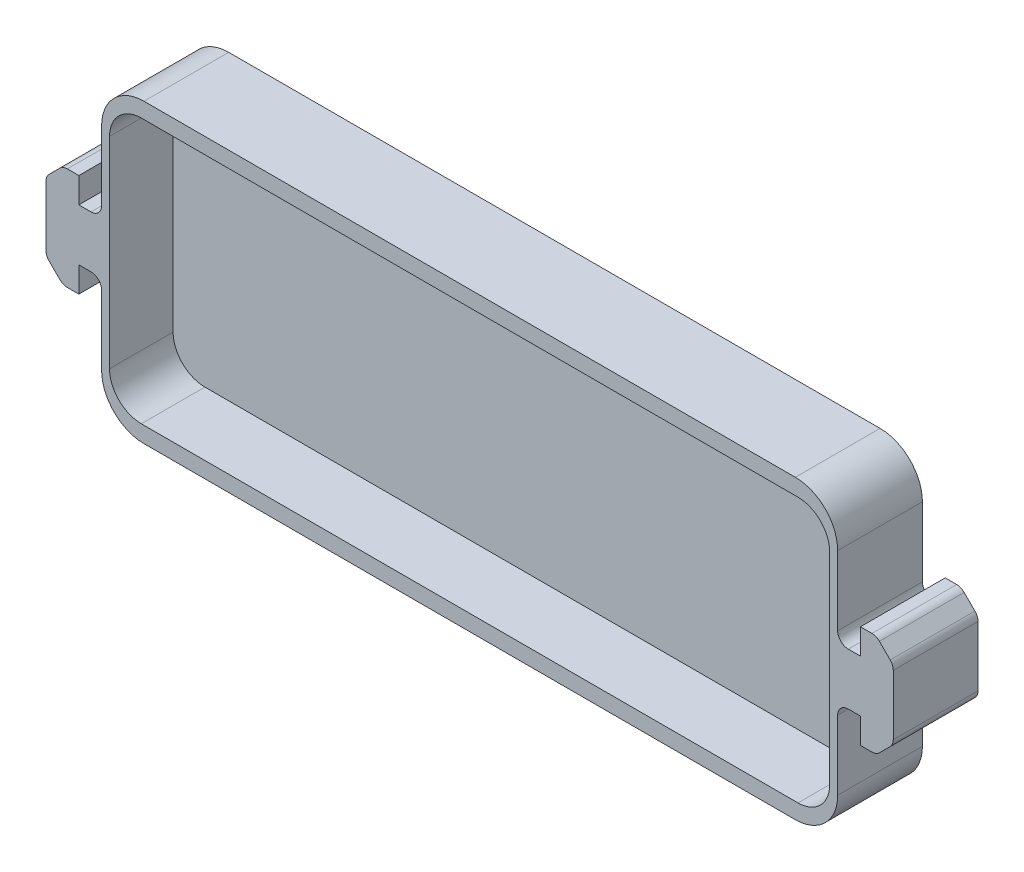
SolidWorks part; units mm, degrees
ref_plane "Front" through (0, 0, 0) normal (0, 0, 1) x (1, 0, 0)
ref_plane "Top" through (0, 0, 0) normal (0, 1, 0) x (1, 0, 0)
ref_plane "Right" through (0, 0, 0) normal (1, 0, 0) x (0, 0, -1)
sketch "Esquisse1" plane through (0, 0, 0) normal (0, 0, 1) x (1, 0, 0)
  line L1 (-34.75, -14) -> (0, -14)
  line L2 (-34.75, -14) -> (-34.75, 14)
  line L3 (-34.75, 14) -> (0, 14)
  line L4 (0, -14) -> (0, 14)
  point P5 (0, 0)
  dimension "D1" = 34.75
  dimension "D2" = 28
extrude "Boss.-Extru.1" add sketch "Esquisse1" along normal blind 8
fillet "Congé1" radius 4 2 edges at (-34.75, 14, 4) (-34.75, -14, 4)
sketch "Esquisse3" plane through (0, 0, 8) normal (0, 0, 1) x (1, 0, 0)
  line L0 (0, -12.5) -> (0, 12.5)
  line L1 (-31, 12.5) -> (0, 12.5)
  line L2 (-34, 9.5) -> (-34, -9.5)
  line L3 (-31, -12.5) -> (0, -12.5)
  line L5 (0, -12.5) -> (0, 12.5) construction
  arc A2 (-34, -9.5) -> (-31, -12.5) centre (-31, -9.5) ccw
  arc A3 (-31, 12.5) -> (-34, 9.5) centre (-31, 9.5) ccw
  point P1 (0, 0)
  point P48 (0, 0)
  dimension "D1" = 34
  dimension "D2" = 25
extrude "Enlèv. mat.-Extru.1" cut sketch "Esquisse3" against normal offset from surface (6 mm away) 2 up to face at (-22.1095, 0, 0)
sketch "Esquisse5" plane through (0, 0, 0) normal (0, 0, 1) x (1, 0, 0)
  line L0 (-34.75, 2.45) -> (-36.9, 2.45)
  line L1 (-34.75, 10) -> (-34.75, -10) construction
  line L2 (-36.9, 2.45) -> (-36.9, 4.85)
  line L3 (-36.9, 4.85) -> (-38.4, 4.85)
  line L4 (-38.4, 4.85) -> (-40, 3.25)
  line L5 (-40, 3.25) -> (-40, -3.25)
  line L6 (-40, -3.25) -> (-38.4, -4.85)
  line L7 (-38.4, -4.85) -> (-36.9, -4.85)
  line L8 (-36.9, -4.85) -> (-36.9, -2.45)
  line L9 (-36.9, -2.45) -> (-34.75, -2.45)
  line L10 (-34.75, -2.45) -> (-34.75, 2.45)
  line L11 (-34.75, 10) -> (-34.75, -10) construction
  point P5 (-35, 0)
  point P13 (-34.75, 0)
  point P14 (-35, -1.3408)
  point P15 (-36.4595, -3.4579)
  point P16 (-39.7326, -2.3682)
  point P19 (0, 0)
  point P21 (-38.2753, -4.8345)
  point P22 (-39.815, 3.0507)
  dimension "D1" = 2.15
  dimension "D2" = 4.9
  dimension "D3" = 1.5
  dimension "D4" = 6.5
  dimension "D5" = 5.25
extrude "Boss.-Extru.2" add sketch "Esquisse5" along normal up to surface (8 mm away) up to face at (-21.9916, 0, 8)
fillet "Congé2" radius 1 6 edges at (-34.75, 2.45, 4) (-34.75, -2.45, 4) (-38.4, -4.85, 4) (-38.4, 4.85, 4) (-40, 3.25, 4) (-40, -3.25, 4)
mirror "Symétrie1" about plane through (0, -14, 8) normal (-1, 0, 0) of "Congé2", "Boss.-Extru.1", "Congé1", "Enlèv. mat.-Extru.1", "Boss.-Extru.2"
